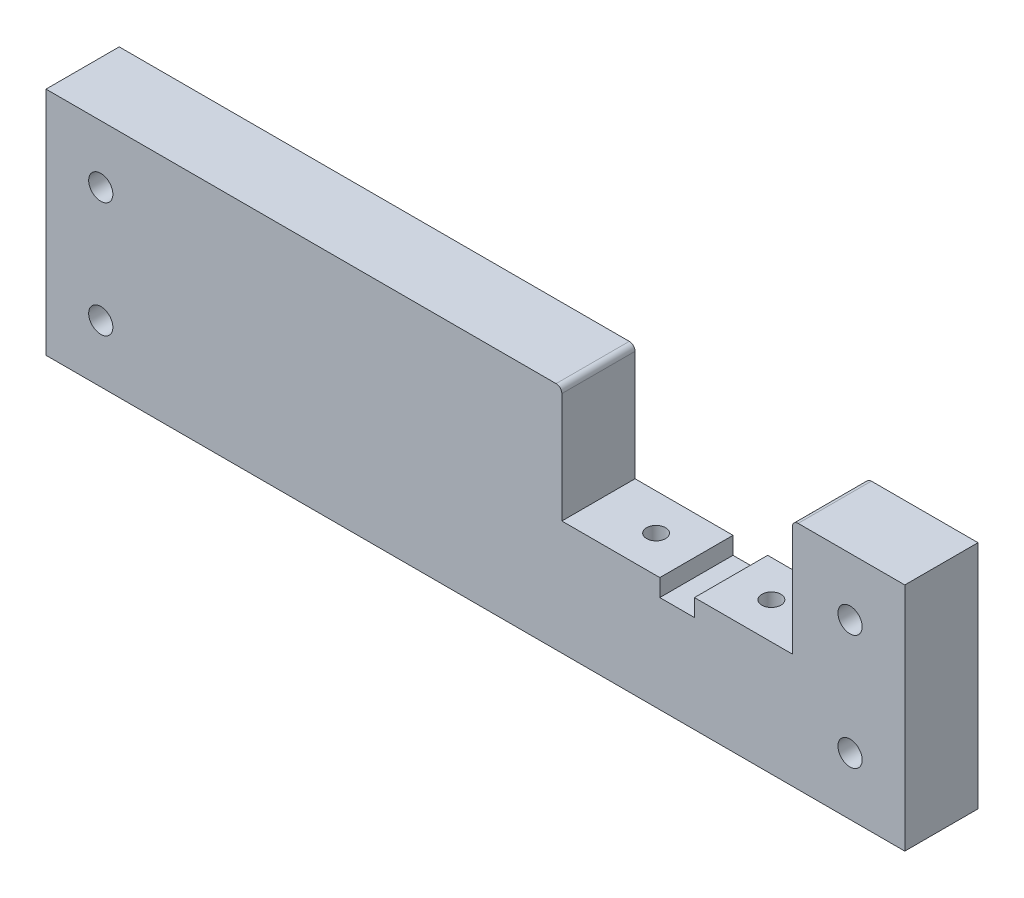
SolidWorks part; units mm, degrees
material "6061-T6 (SS)"
ref_plane "Front Plane" through (0, 0, 0) normal (0, 0, 1) x (1, 0, 0)
ref_plane "Top Plane" through (0, 0, 0) normal (0, 1, 0) x (1, 0, 0)
ref_plane "Right Plane" through (0, 0, 0) normal (1, 0, 0) x (0, 0, -1)
sketch "Sketch1" plane through (0, 0, 0) normal (0, 0, 1) x (1, 0, 0)
  line L0 (-65, 30) -> (-65, 10) construction
  line L1 (-74.5, 40) -> (74.5, 40)
  line L2 (-74.5, 40) -> (-74.5, 0)
  line L3 (-74.5, 0) -> (74.5, 0)
  line L4 (74.5, 40) -> (74.5, 0)
  line L5 (31.995, 22.86) -> (38.005, 22.86)
  line L6 (31.995, 22.86) -> (31.995, 16.85)
  line L7 (31.995, 16.85) -> (38.005, 16.85)
  line L8 (38.005, 22.86) -> (38.005, 16.85)
  line L9 (32, 22.855) -> (38, 22.855) construction
  line L10 (32, 22.855) -> (32, 16.855) construction
  line L11 (32, 16.855) -> (38, 16.855) construction
  line L12 (38, 22.855) -> (38, 16.855) construction
  line L13 (0, 0) -> (0, 40) construction
  line L14 (38.005, 19.855) -> (55, 19.855)
  line L15 (31.995, 19.855) -> (15, 19.855)
  line L16 (15, 19.855) -> (15, 40)
  line L17 (55, 19.855) -> (55, 40)
  circle A0 centre (-65, 30) radius 2.5 construction
  circle A1 centre (-65, 10) radius 2.5 construction
  circle A2 centre (65, 10) radius 2.5 construction
  circle A3 centre (65, 30) radius 2.5 construction
  point P10 (0, 0)
  point P14 (35, 22.855)
  point P15 (35, 22.86)
  point P16 (32, 19.855)
  point P17 (31.995, 19.855)
  point P34 (38.005, 19.855)
  dimension "D8" = 5
  dimension "D1" = 6.01
  dimension "D2" = 149
  dimension "D3" = 40
  dimension "D4" = 16.85
  dimension "D5" = 32
  dimension "D6" = 6
  dimension "D7" = 20
  dimension "D9" = 10
  dimension "D10" = 65
  dimension "D11" = 40
extrude "Boss-Extrude1" add sketch "Sketch1" against normal blind 12.7 contours L17 L14 L8 L7 L6 L15 L16 L1 L2 L3 L4
sketch "Sketch4" plane through (0, 0, 0) normal (0, -1, 0) x (1, 0, 0)
  line L0 (-60, -6.35) -> (60, -6.35) construction
  line L2 (-74.5, 0) -> (74.5, 0)
  line L3 (-74.5, 0) -> (-74.5, -12.7)
  line L4 (-74.5, -12.7) -> (74.5, -12.7)
  line L5 (74.5, 0) -> (74.5, -12.7)
  circle A0 centre (0, -6.35) radius 2.5 construction
  circle A1 centre (60, -6.35) radius 2.5 construction
  circle A2 centre (-60, -6.35) radius 2.5 construction
  point P6 (0, -6.35)
  point P14 (74.5, -6.35)
  dimension "D1" = 5
  dimension "D2" = 120
sketch "Sketch8" plane through (0, 19.855, 0) normal (0, 1, 0) x (1, 0, 0)
  line L0 (31.995, 0) -> (15, 0) construction
  line L1 (15, 0) -> (15, 12.7) construction
  line L2 (15, 12.7) -> (31.995, 12.7) construction
  line L3 (31.995, 12.7) -> (31.995, 0) construction
  line L4 (55, 0) -> (38.005, 0) construction
  line L5 (38.005, 0) -> (38.005, 12.7) construction
  line L6 (38.005, 12.7) -> (55, 12.7) construction
  line L7 (55, 12.7) -> (55, 0) construction
  line L8 (31.995, 0) -> (15, 0) construction
  line L9 (15, 0) -> (15, 12.7) construction
  line L10 (15, 12.7) -> (31.995, 12.7) construction
  line L11 (31.995, 12.7) -> (31.995, 0) construction
  line L12 (55, 0) -> (38.005, 0) construction
  line L13 (38.005, 0) -> (38.005, 12.7) construction
  line L14 (38.005, 12.7) -> (55, 12.7) construction
  line L15 (55, 12.7) -> (55, 0) construction
  line L16 (25, 6.35) -> (45, 6.35)
  line L17 (31.995, 12.7) -> (38.005, 12.7)
  circle A0 centre (45, 6.35) radius 2 construction
  circle A1 centre (25, 6.35) radius 2 construction
  point P4 (35, 6.35)
  point P5 (35, 12.7)
  point P8 (25.143, 6.35)
  point P10 (31.995, 6.35)
  dimension "D1" = 4
  dimension "D2" = 20
  dimension "D4" = 10
  dimension "D3" = 10
hole_wizard "Tap Drill for M4x0.7 Tap1" positions "3DSketch3" profile "Sketch9" hole size "M4x0.7" standard "ANSI Metric"
sketch3d "3DSketch3"
  point P0 (25, 19.855, -6.35)
  point P2 (45, 19.855, -6.35)
sketch "Sketch9" plane through (25, 19.855, -6.35) normal (1, 0, 0) x (0, 0, 1)
  line L0 (0, 0) -> (0, 5.9914)
  line L1 (0, 5.9914) -> (1.65, 5)
  line L2 (1.65, 5) -> (1.65, 0)
  line L5 (1.65, 0) -> (0, 0)
  line L10 (0, 5.9914) -> (-1.65, 5) construction
  line L11 (0, -6.35) -> (0, 107.95) construction
  dimension "Hole Dia." = 3.3
  dimension "Hole Depth" = 5
  dimension "Drill Angle" = 118
hole_wizard "Tap Drill for M5x0.8 Tap3" positions "3DSketch4" profile "Sketch10" hole size "M5x0.8" standard "ANSI Metric" end condition up to next
sketch3d "3DSketch4"
  point P0 (-65, 30, 0)
  point P2 (-65, 10, 0)
  point P4 (65, 10, 0)
  point P6 (65, 30, 0)
sketch "Sketch10" plane through (-65, 30, 0) normal (1, 0, 0) x (0, -1, 0)
  line L0 (0, 0) -> (0, 12.7)
  line L1 (0, 12.7) -> (2.1, 12.7)
  line L2 (2.1, 12.7) -> (2.1, 0)
  line L5 (2.1, 0) -> (0, 0)
  line L11 (0, -6.35) -> (0, 107.95) construction
  dimension "Thru Hole Dia." = 4.2
  dimension "Thru Hole Depth" = 12.7
hole_wizard "Tap Drill for M5x0.8 Tap2" positions "3DSketch2" profile "Sketch5" hole size "M5x0.8" standard "ANSI Metric"
sketch3d "3DSketch2"
  point P0 (-60, 0, -6.35)
  point P2 (0, 0, -6.35)
  point P4 (60, 0, -6.35)
sketch "Sketch5" plane through (-60, 0, -6.35) normal (1, 0, 0) x (0, 0, -1)
  line L0 (0, 0) -> (0, 8.2618)
  line L1 (0, 8.2618) -> (2.1, 7)
  line L2 (2.1, 7) -> (2.1, 0)
  line L5 (2.1, 0) -> (0, 0)
  line L10 (0, 8.2618) -> (-2.1, 7) construction
  line L11 (0, -6.35) -> (0, 107.95) construction
  dimension "Hole Dia." = 4.2
  dimension "Hole Depth" = 7
  dimension "Drill Angle" = 118
fillet "Fillet1" radius 1 2 edges at (15, 40, -6.35) (55, 40, -6.35)
